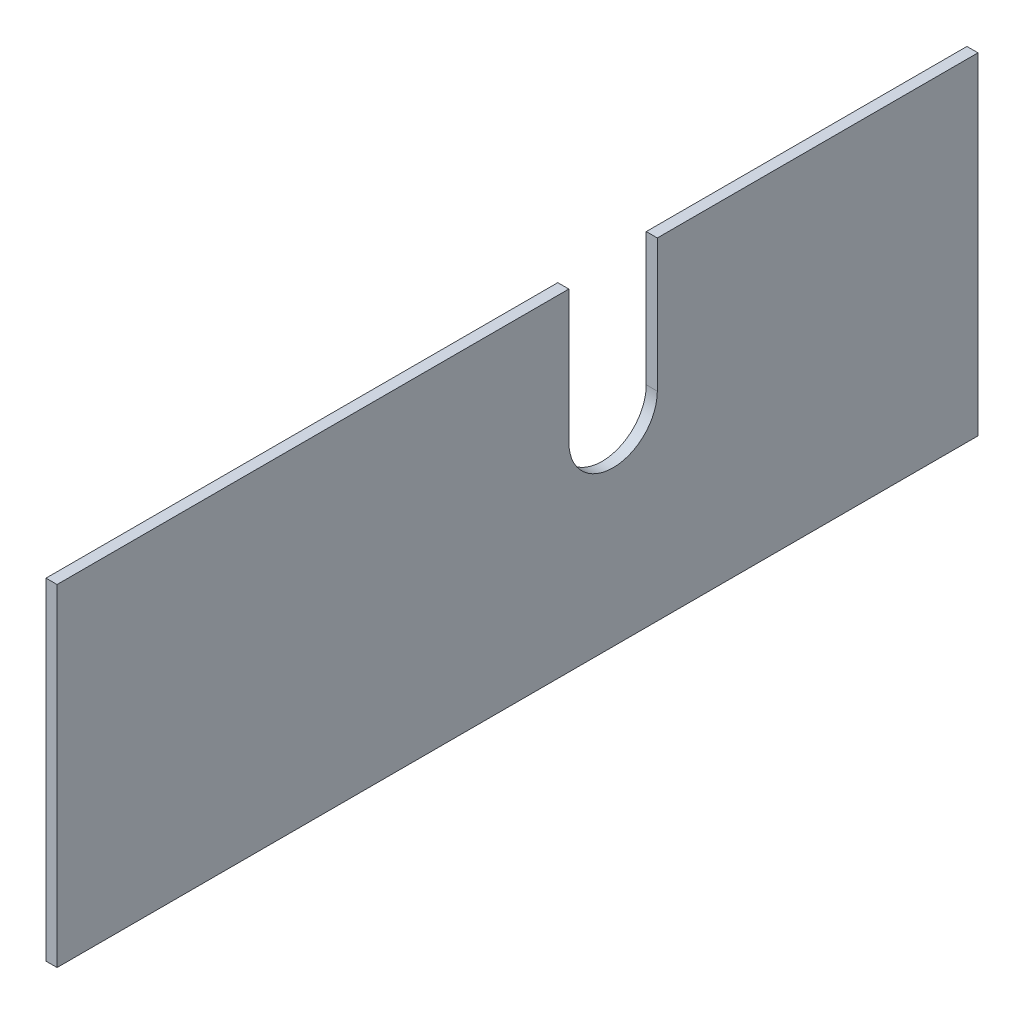
SolidWorks part; units mm, degrees
ref_plane "Front Plane" through (0, 0, 0) normal (0, 0, 1) x (1, 0, 0)
ref_plane "Top Plane" through (0, 0, 0) normal (0, 1, 0) x (1, 0, 0)
ref_plane "Right Plane" through (0, 0, 0) normal (1, 0, 0) x (0, 0, -1)
sketch "Sketch1" plane through (0, 0, 0) normal (1, 0, 0) x (0, 0, -1)
  line L1 (-41.64, -15) -> (41.64, -15)
  line L2 (-41.64, -15) -> (-41.64, 15)
  line L3 (-41.64, 15) -> (41.64, 15)
  line L4 (41.64, -15) -> (41.64, 15)
  line L5 (-41.64, -15) -> (41.64, 15) construction
  line L6 (-41.64, 15) -> (41.64, -15) construction
  point P0 (0, 0)
  dimension "D1" = 83.28
  dimension "D2" = 30
extrude "Boss-Extrude1" add sketch "Sketch1" along normal blind 1
sketch "Sketch2" [suppressed] plane through (1, 0, 0) normal (1, 0, 0) x (0, 0, -1)
  line L0 (0, 15) -> (0, -15) construction
  line L1 (41.64, 15) -> (-41.64, 15) construction
  line L2 (-41.64, -15) -> (41.64, -15) construction
  line L3 (-3.54, 2) -> (-3.54, -8) construction
  line L4 (-18.54, 2) -> (-3.54, 2)
  line L5 (-18.54, 2) -> (-18.54, -15)
  line L6 (-18.54, -15) -> (-3.54, -15)
  line L7 (-3.54, 2) -> (-3.54, -15)
extrude "Cut-Extrude1" [suppressed] cut sketch "Sketch2" against normal through all
fillet "Fillet1" [suppressed] radius 1
sketch "Sketch3" plane through (1, 0, 0) normal (1, 0, 0) x (0, 0, -1)
  line L0 (41.64, -15) -> (41.64, 15) construction
  line L1 (41.64, 15) -> (-41.64, 15) construction
  line L3 (4.64, 3) -> (12.64, 3)
  line L4 (4.64, 3) -> (4.64, 15)
  line L5 (4.64, 15) -> (12.64, 15)
  line L6 (12.64, 3) -> (12.64, 15)
  circle A0 centre (8.64, 3) radius 4
  line M2 (41.64, 15) -> (-41.64, 15)
  dimension "D1" = 33
  dimension "D2" = 12
  dimension "D3" = 8
extrude "Cut-Extrude2" cut sketch "Sketch3" against normal through all contours A0 L6 L4 M2 | L3 A0 | L3 A0
